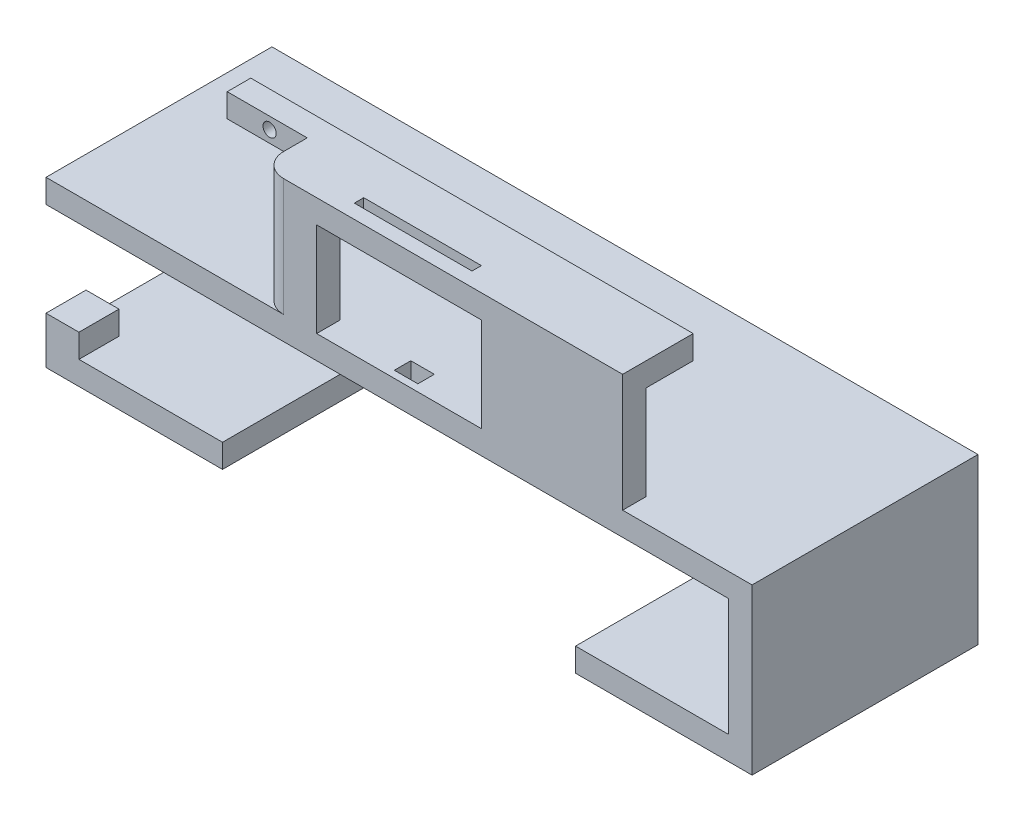
SolidWorks part; units mm, degrees
ref_plane "Alzado" through (0, 0, 0) normal (0, 0, 1) x (1, 0, 0)
ref_plane "Planta" through (0, 0, 0) normal (0, 1, 0) x (1, 0, 0)
ref_plane "Vista lateral" through (0, 0, 0) normal (1, 0, 0) x (0, 0, -1)
sketch "Croquis1" plane through (0, 0, 0) normal (0, 0, 1) x (1, 0, 0)
  line L0 (0, 7.5) -> (0, -7.5) construction
  line L1 (0, 7.5) -> (0, 10.5) construction
  line L3 (-47.5, 10.5) -> (47.5, 10.5)
  line L4 (-47.5, 10.5) -> (-47.5, 7.5)
  line L5 (-47.5, 7.5) -> (47.5, 7.5)
  line L6 (47.5, 10.5) -> (47.5, 7.5)
  line L7 (-47.5, 10.5) -> (47.5, 7.5) construction
  line L8 (-47.5, 7.5) -> (47.5, 10.5) construction
  line L9 (-47.5, 7.5) -> (-40, 7.5)
  line L10 (-47.5, 7.5) -> (-47.5, -7.5)
  line L11 (-47.5, -7.5) -> (-40, -7.5)
  line L12 (-40, 7.5) -> (-40, -7.5)
  line L13 (47.5, 7.5) -> (40, 7.5)
  line L14 (47.5, 7.5) -> (47.5, -7.5)
  line L15 (47.5, -7.5) -> (40, -7.5)
  line L16 (40, 7.5) -> (40, -7.5)
  point P0 (0, 9)
  point P4 (0, 0)
  dimension "D1" = 15
  dimension "D2" = 3
  dimension "D3" = 3
  dimension "D4" = 95
  dimension "D5" = 7.5
  dimension "D6" = 15
  dimension "D7" = 15
  dimension "D8" = 7.5
extrude "Saliente-Extruir1" add sketch "Croquis1" along normal blind 5 contours L5 L16 L15 L14 | L6 L3 L4 L5 | L12 L5 L10 L11
sketch "Croquis2" plane through (0, 0, 0) normal (0, 0, -1) x (-1, 0, 0)
  line L0 (47.5, 10.5) -> (47.5, -7.5) construction
  line L1 (-47.5, 10.5) -> (47.5, 10.5)
  line L2 (-47.5, 10.5) -> (-47.5, 7.5)
  line L3 (-47.5, 7.5) -> (47.5, 7.5)
  line L4 (47.5, 10.5) -> (47.5, 7.5)
extrude "Saliente-Extruir2" add sketch "Croquis2" along normal blind 5
sketch "Croquis5" plane through (47.5, 0, 0) normal (1, 0, 0) x (0, 0, -1)
  line L0 (0, 7.5) -> (0, 10.5) construction
  line L1 (0, 7.5) -> (0, -7.5) construction
  line L2 (-5, 10.5) -> (5, 10.5) construction
  line L5 (0, -7.5) -> (-5, -7.5)
  line L6 (0, -7.5) -> (0, 7.5)
  line L7 (0, 7.5) -> (-5, 7.5)
  line L8 (-5, -7.5) -> (-5, 7.5)
extrude "Cortar-Extruir2" cut sketch "Croquis5" against normal through all
sketch "Croquis6" plane through (47.5, 0, 0) normal (1, 0, 0) x (0, 0, -1)
  line L1 (-5, 10.5) -> (-10, 10.5)
  line L2 (-5, 10.5) -> (-5, -12.5)
  line L3 (-5, -12.5) -> (-10, -12.5)
  line L4 (-10, 10.5) -> (-10, -12.5)
  dimension "D1" = 5
  dimension "D2" = 23
extrude "Saliente-Extruir3" add sketch "Croquis6" against normal through all
sketch "Croquis7" plane through (0, 0, 10) normal (0, 0, 1) x (1, 0, 0)
  line L0 (-47.5, 10.5) -> (-47.5, 7.5) construction
  line L1 (-47.5, 10.5) -> (-47.5, -12.5) construction
  line L2 (-47.5, 7.5) -> (47.5, 7.5) construction
  line L3 (-47.5, -12.5) -> (-17.5, -12.5) construction
  line L4 (-47.5, -12.5) -> (47.5, -12.5) construction
  line L5 (47.5, -12.5) -> (17.5, -12.5) construction
  line L7 (-17.5, -12.5) -> (17.5, -12.5)
  line L8 (-17.5, -12.5) -> (-17.5, 7.5)
  line L9 (-17.5, 7.5) -> (17.5, 7.5)
  line L10 (17.5, -12.5) -> (17.5, 7.5)
  dimension "D1" = 30
  dimension "D2" = 30
extrude "Cortar-Extruir3" cut sketch "Croquis7" against normal through all
sketch "Croquis9" plane through (0, 0, 10) normal (0, 0, 1) x (1, 0, 0)
  line L0 (-32.5, -12.5) -> (-32.5, -42.5) construction
  line L1 (-47.5, -12.5) -> (-17.5, -12.5) construction
  line L2 (0, 0) -> (-85, 0) construction
  line L3 (17.5, 7.5) -> (-17.5, 7.5) construction
  line L4 (-85, -12.5) -> (80, -12.5)
  line L5 (-85, -12.5) -> (-85, -52.5)
  line L6 (-85, -52.5) -> (80, -52.5)
  line L7 (80, -12.5) -> (80, -52.5)
  line L8 (47.5, 10.5) -> (47.5, -12.5) construction
  dimension "D1" = 85
  dimension "D2" = 165
  dimension "D3" = 40
  dimension "D4" = 20
  dimension "D5" = 32.5
extrude "Saliente-Extruir4" add sketch "Croquis9" against normal blind 50 contours L5 L4 L7 L6
sketch "Croquis15" plane through (0, 10.5, 0) normal (0, 1, 0) x (1, 0, 0)
  line L1 (-47.5, 5) -> (47.5, 5)
  line L2 (-47.5, 5) -> (-47.5, -10)
  line L3 (-47.5, -10) -> (47.5, -10)
  line L4 (47.5, 5) -> (47.5, -10)
extrude "Saliente-Extruir7" add sketch "Croquis15" along normal blind 2
sketch "Croquis16" plane through (0, 0, -5) normal (0, 0, -1) x (-1, 0, 0)
  line L0 (-47.5, 10) -> (47.5, 10) construction
  line L1 (-47.5, 12.5) -> (-47.5, 7.5) construction
  line L2 (47.5, 7.5) -> (47.5, 12.5) construction
  line L3 (-37.5, 12.5) -> (-37.5, 7.5) construction
  line L4 (-47.5, 12.5) -> (47.5, 12.5) construction
  line L5 (-17.5, 7.5) -> (-47.5, 7.5) construction
  line L6 (0, 12.5) -> (0, 7.5) construction
  line L7 (-47.5, 7.5) -> (47.5, 7.5) construction
  circle A0 centre (-37.5, 10) radius 1.4
  circle A1 centre (37.5, 10) radius 1.4
  dimension "D2" = 2.8
  dimension "D1" = 10
extrude "Cortar-Extruir7" cut sketch "Croquis16" against normal blind 5
sketch "Croquis18" plane through (0, 12.5, 0) normal (0, 1, 0) x (1, 0, 0)
  line L0 (0, -10) -> (0, -7) construction
  line L1 (-47.5, -10) -> (47.5, -10) construction
  line L2 (0, -7) -> (0, -5) construction
  line L3 (-47.5, 5) -> (-47.5, -10) construction
  line L4 (-12.5, -7) -> (12.5, -7)
  line L5 (-12.5, -7) -> (-12.5, -5)
  line L6 (-12.5, -5) -> (12.5, -5)
  line L7 (12.5, -7) -> (12.5, -5)
  line L8 (-12.5, -7) -> (12.5, -5) construction
  line L9 (-12.5, -5) -> (12.5, -7) construction
  point P6 (0, -6)
  dimension "D1" = 35
  dimension "D2" = 2
extrude "Cortar-Extruir9" cut sketch "Croquis18" against normal up to surface (5 mm away) up to face at (0, 7.5, 3.75)
sketch "Croquis19" plane through (0, 0, 10) normal (0, 0, 1) x (1, 0, 0)
  line L0 (-17.5, -12.5) -> (17.5, -12.5) construction
  line L4 (-70, -42.5) -> (70, -42.5)
  line L5 (-70, -42.5) -> (-70, -17.5)
  line L6 (-70, -17.5) -> (70, -17.5)
  line L7 (70, -42.5) -> (70, -17.5)
  line L8 (-70, -42.5) -> (70, -17.5) construction
  line L9 (-70, -17.5) -> (70, -42.5) construction
  point P6 (0, -30)
  dimension "D1" = 140
  dimension "D2" = 25
  dimension "D3" = 5
extrude "Cortar-Extruir10" cut sketch "Croquis19" against normal blind 43 and the other way through all
sketch "Croquis20" plane through (0, 0, 10) normal (0, 0, 1) x (1, 0, 0)
  line L0 (-85, -52.5) -> (80, -52.5) construction
  line L1 (-85, -12.5) -> (-75, -12.5)
  line L2 (-85, -12.5) -> (-85, -52.5)
  line L3 (-85, -52.5) -> (-75, -52.5)
  line L4 (-75, -12.5) -> (-75, -52.5)
  line L5 (70, -42.5) -> (-70, -42.5) construction
  line L6 (80, -12.5) -> (75, -12.5)
  line L7 (80, -12.5) -> (80, -52.5)
  line L8 (80, -52.5) -> (75, -52.5)
  line L9 (75, -12.5) -> (75, -52.5)
  line L10 (-85, -52.5) -> (80, -52.5)
  line L11 (-85, -52.5) -> (-85, -47.5)
  line L12 (-85, -47.5) -> (80, -47.5)
  line L13 (80, -52.5) -> (80, -47.5)
  line M12 (-47.5, -12.5) -> (-85, -12.5)
  line M13 (-85, -12.5) -> (-85, -52.5)
  line M14 (-85, -52.5) -> (80, -52.5)
  line M15 (80, -52.5) -> (80, -12.5)
  dimension "D1" = 10
  dimension "D2" = 5
  dimension "D3" = 5
extrude "Cortar-Extruir11" cut sketch "Croquis20" against normal through all contours L12 L4 M13 M12 | L12 L2 L4 M14 | L12 L4 L9 M14 | L12 L9 M14 M15
sketch "Croquis23" plane through (75, 0, 0) normal (1, 0, 0) x (0, 0, -1)
  line L0 (-10, -47.5) -> (40, -47.5) construction
  line L1 (40, -12.5) -> (38, -12.5)
  line L2 (40, -12.5) -> (40, -47.5)
  line L3 (40, -47.5) -> (38, -47.5)
  line L4 (38, -12.5) -> (38, -47.5)
  dimension "D1" = 2
extrude "Cortar-Extruir12" cut sketch "Croquis23" against normal through all
sketch "Croquis24" plane through (-75, 0, 0) normal (-1, 0, 0) x (0, 0, 1)
  line L1 (10, -17.5) -> (-33, -17.5)
  line L2 (10, -17.5) -> (10, -42.5)
  line L3 (10, -42.5) -> (-33, -42.5)
  line L4 (-33, -17.5) -> (-33, -42.5)
  line L5 (-38, -47.5) -> (10, -47.5) construction
  line L6 (-38, -12.5) -> (-38, -47.5) construction
  line L7 (-11.5, -42.5) -> (-11.5, -32.5) construction
  line L8 (10, -32.5) -> (-33, -32.5) construction
  line L10 (-33, -32.5) -> (-24.5, -32.5)
  line L11 (-33, -32.5) -> (-33, -42.5)
  line L12 (-33, -42.5) -> (-24.5, -42.5)
  line L13 (-24.5, -32.5) -> (-24.5, -42.5)
  line L14 (10, -32.5) -> (1.5, -32.5)
  line L15 (10, -32.5) -> (10, -42.5)
  line L16 (10, -42.5) -> (1.5, -42.5)
  line L17 (1.5, -32.5) -> (1.5, -42.5)
  point P14 (-11.5, -32.5)
  dimension "D1" = 5
  dimension "D2" = 5
  dimension "D3" = 10
  dimension "D4" = 8.5
  dimension "D5" = 8.5
extrude "Cortar-Extruir13" cut sketch "Croquis24" against normal up to surface (5 mm away) contours L17 L14 L2 L1 L4 L10 L13 L3 up to face at (-70, -30, -11.5)
sketch "Croquis25" plane through (0, -42.5, 0) normal (0, 1, 0) x (1, 0, 0)
  line L0 (0, -10) -> (0, -15) construction
  line L1 (-47.5, -10) -> (47.5, -10) construction
  line L2 (0, -15) -> (0, -18) construction
  line L4 (-2.5, -15) -> (2.5, -15)
  line L5 (-2.5, -15) -> (-2.5, -10)
  line L6 (-2.5, -10) -> (2.5, -10)
  line L7 (2.5, -15) -> (2.5, -10)
  line L8 (-2.5, -15) -> (2.5, -10) construction
  line L9 (-2.5, -10) -> (2.5, -15) construction
  line L10 (-4, -8.5) -> (4, -8.5)
  line L11 (-4, -8.5) -> (-4, -16.5)
  line L12 (-4, -16.5) -> (4, -16.5)
  line L13 (4, -8.5) -> (4, -16.5)
  line L14 (-4, -8.5) -> (4, -16.5) construction
  line L15 (-4, -16.5) -> (4, -8.5) construction
  point P6 (0, -12.5)
  point P11 (0, -12.5)
  dimension "D1" = 5
  dimension "D2" = 3
  dimension "D3" = 5
  dimension "D4" = 8
  dimension "D5" = 8
extrude "Saliente-Extruir8" add sketch "Croquis25" against normal through all contours L11 L10 L13 L12 | L5 L4 L7 L6
sketch "Croquis27" plane through (0, -12.5, 0) normal (0, 1, 0) x (1, 0, 0)
  line L0 (0, -10) -> (0, -3.5) construction
  line L1 (-17.5, -10) -> (17.5, -10) construction
  line L3 (-2.5, -5) -> (2.5, -5)
  line L4 (-2.5, -5) -> (-2.5, -8.5)
  line L5 (-2.5, -8.5) -> (2.5, -8.5)
  line L6 (2.5, -5) -> (2.5, -8.5)
  line L7 (-2.5, -5) -> (2.5, -8.5) construction
  line L8 (-2.5, -8.5) -> (2.5, -5) construction
  point P5 (0, -6.75)
  dimension "D1" = 5
  dimension "D2" = 3.5
  dimension "D3" = 1.5
extrude "Cortar-Extruir14" cut sketch "Croquis27" against normal up to surface (5 mm away) up to face at (-2.5, -17.5, -11.5)
sketch "Croquis28" plane through (-70, 0, 0) normal (1, 0, 0) x (0, 0, -1)
  line L0 (-10, -42.5) -> (-1.5, -42.5) construction
  line L1 (-1.5, -42.5) -> (-1.5, -32.5) construction
  line L2 (-1.5, -32.5) -> (-10, -32.5) construction
  line L3 (-10, -32.5) -> (-10, -42.5) construction
  line L4 (24.5, -32.5) -> (24.5, -42.5) construction
  line L5 (24.5, -42.5) -> (33, -42.5) construction
  line L6 (33, -42.5) -> (33, -32.5) construction
  line L7 (33, -32.5) -> (24.5, -32.5) construction
  line L8 (-10, -42.5) -> (-1.5, -42.5)
  line L9 (-1.5, -42.5) -> (-1.5, -32.5)
  line L10 (-1.5, -32.5) -> (-10, -32.5)
  line L11 (-10, -32.5) -> (-10, -42.5)
  line L12 (24.5, -32.5) -> (24.5, -42.5)
  line L13 (24.5, -42.5) -> (33, -42.5)
  line L14 (33, -42.5) -> (33, -32.5)
  line L15 (33, -32.5) -> (24.5, -32.5)
extrude "Saliente-Extruir9" add sketch "Croquis28" along normal blind 2
sketch "Croquis29" plane through (0, 0, 16.5) normal (0, 0, 1) x (1, 0, 0)
  line L0 (-47.5, -12.5) -> (-47.5, -47.5) construction
  line L1 (-75, -47.5) -> (-4, -47.5) construction
  line L2 (-37.5, -17.5) -> (-37.5, -47.5) construction
  line L3 (70, -17.5) -> (-75, -17.5) construction
  line L4 (4, -47.5) -> (75, -47.5) construction
  line L5 (-37.5, -17.5) -> (37.5, -17.5)
  line L6 (-37.5, -17.5) -> (-37.5, -47.5)
  line L7 (-37.5, -47.5) -> (37.5, -47.5)
  line L8 (37.5, -17.5) -> (37.5, -47.5)
  line L9 (-37.5, -17.5) -> (37.5, -47.5) construction
  line L10 (-37.5, -47.5) -> (37.5, -17.5) construction
  line L11 (47.5, -12.5) -> (47.5, -47.5) construction
  point P11 (0, -32.5)
  dimension "D1" = 10
  dimension "D2" = 10
extrude "Cortar-Extruir15" cut sketch "Croquis29" against normal through all
sketch "Croquis30" plane through (-75, 0, 0) normal (-1, 0, 0) x (0, 0, 1)
  line L0 (1.5, -32.5) -> (1.5, -42.5) construction
  line L1 (10, -32.5) -> (1.5, -32.5)
  line L2 (10, -32.5) -> (10, -37.5)
  line L3 (10, -37.5) -> (1.5, -37.5)
  line L4 (1.5, -32.5) -> (1.5, -37.5)
  line L5 (10, -32.5) -> (1.5, -37.5) construction
  line L6 (10, -37.5) -> (1.5, -32.5) construction
  point P4 (5.75, -35)
extrude "Cortar-Extruir16" cut sketch "Croquis30" against normal up to surface (7 mm away) up to face at (-68, -37.5, 5.75)
sketch "Croquis31" plane through (0, 0, 10) normal (0, 0, 1) x (1, 0, 0)
  line L1 (-47.5, 12.5) -> (-29.5, 12.5)
  line L2 (-47.5, 12.5) -> (-47.5, -12.5)
  line L3 (-47.5, -12.5) -> (-29.5, -12.5)
  line L4 (-29.5, 12.5) -> (-29.5, -12.5)
  line L5 (-47.5, 12.5) -> (-29.5, -12.5) construction
  line L6 (-47.5, -12.5) -> (-29.5, 12.5) construction
  point P4 (-38.5, 0)
  dimension "D1" = 18
  dimension "D2" = 25
extrude "Cortar-Extruir17" cut sketch "Croquis31" against normal blind 10
sketch "Croquis32" plane through (-47.5, 0, 0) normal (-1, 0, 0) x (0, 0, 1)
  line L4 (0, 7.5) -> (0, 12.5)
  line L5 (0, 12.5) -> (-5, 12.5)
  line L6 (-5, 12.5) -> (-5, 7.5)
  line L7 (-5, 7.5) -> (0, 7.5)
  line L8 (0, 7.5) -> (0, 12.5)
  line L9 (0, 12.5) -> (-5, 12.5)
  line L10 (-5, 12.5) -> (-5, 7.5)
  line L11 (-5, 7.5) -> (0, 7.5)
  dimension "D1" = 0
extrude "Cortar-Extruir18" cut sketch "Croquis32" against normal blind 1
fillet "Redondeo4" radius 5 1 edges at (-29.5, 0, 10)
